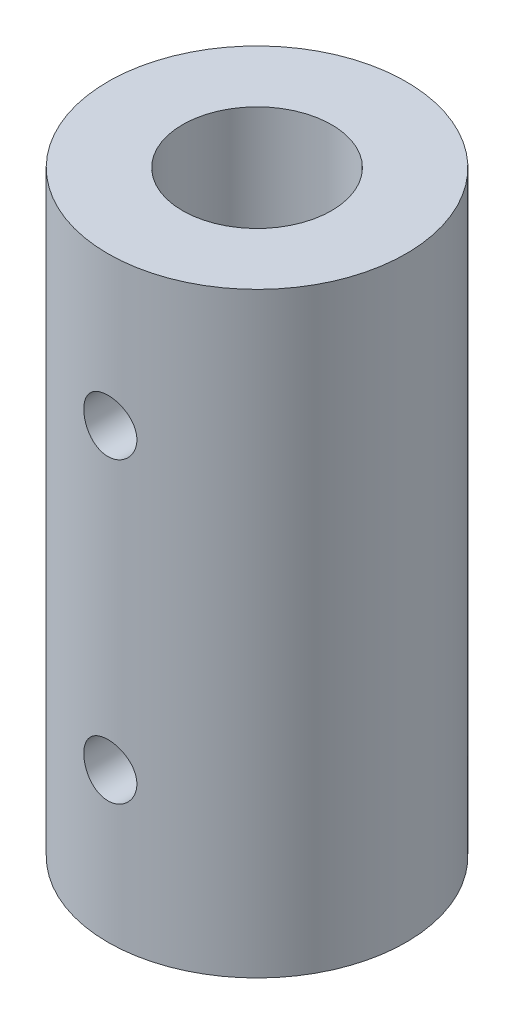
SolidWorks part; units mm, degrees
material "Brass"
ref_plane "Front Plane" through (0, 0, 0) normal (0, 0, 1) x (1, 0, 0)
ref_plane "Top Plane" through (0, 0, 0) normal (0, 1, 0) x (1, 0, 0)
ref_plane "Right Plane" through (0, 0, 0) normal (1, 0, 0) x (0, 0, -1)
sketch "Sketch1" plane through (0, 0, 0) normal (0, 1, 0) x (1, 0, 0)
  circle A0 centre (0, 0) radius 6.35
  dimension "D1" = 12.7
extrude "Boss-Extrude1" add sketch "Sketch1" along normal blind 25.4 contours A0
sketch "Sketch3" plane through (0, 0, 0) normal (0, -1, 0) x (1, 0, 0)
  circle A0 centre (0, 0) radius 4
  dimension "D1" = 8
extrude "Cut-Extrude2" cut sketch "Sketch3" against normal blind 12.7 and the other way through all contours A0
ref_plane "Plane1" through (0, 0, 6.35) normal (0, 0, 1) x (1, 0, 0)
sketch "Sketch6" plane through (0, 0, 0) normal (0, -1, 0) x (-1, 0, 0)
  circle A0 centre (0, 0) radius 4.0005
extrude "Cut-Extrude5" cut sketch "Sketch6" against normal blind 12.7
sketch "Sketch4" plane through (0, 0, 6.35) normal (0, 0, 1) x (1, 0, 0)
  line L0 (6.35, 25.4) -> (-6.35, 25.4) construction
  line L1 (-6.35, 0) -> (6.35, 0) construction
  line L2 (0, 0) -> (0, 25.4) construction
  circle A0 centre (0, 6.35) radius 1.1303
  circle A1 centre (0, 19.05) radius 1.1303
  dimension "D1" = 2.2606
  dimension "D2" = 6.35
  dimension "D3" = 6.35
extrude "Cut-Extrude3" cut sketch "Sketch4" against normal blind 6.35
sketch "Sketch7" plane through (0, 25.4, 0) normal (0, 1, 0) x (1, 0, 0)
  circle A0 centre (0, 0) radius 3.175
  dimension "D1" = 6.35
extrude "Cut-Extrude6" cut sketch "Sketch7" against normal blind 12.7
sketch "Sketch8" [suppressed] plane through (0, 25.4, 0) normal (0, 1, 0) x (1, 0, 0)
  circle A0 centre (0, 0) radius 4
  dimension "D1" = 8
extrude "Cut-Extrude7" [suppressed] cut sketch "Sketch8" against normal blind 12.7 contours A0
